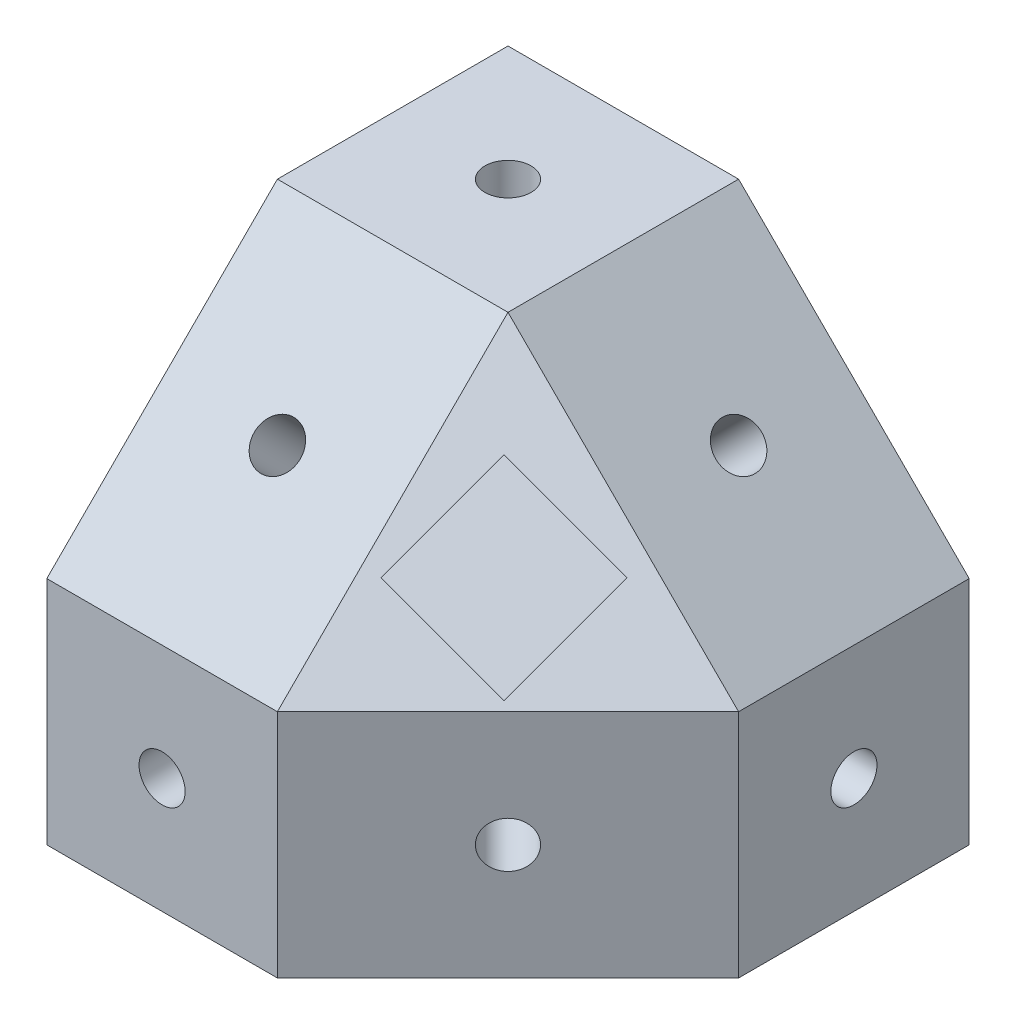
SolidWorks part; units mm, degrees
ref_plane "Front Plane" through (0, 0, 0) normal (0, 0, 1) x (1, 0, 0)
ref_plane "Top Plane" through (0, 0, 0) normal (0, 1, 0) x (1, 0, 0)
ref_plane "Right Plane" through (0, 0, 0) normal (1, 0, 0) x (0, 0, -1)
sketch "Sketch1" plane through (0, 0, 0) normal (0, 0, 1) x (1, 0, 0)
  line L1 (0, 0) -> (30, 0)
  line L2 (0, 0) -> (0, 30)
  line L3 (0, 30) -> (30, 30)
  line L4 (30, 0) -> (30, 30)
  dimension "D1" = 30
  dimension "D2" = 30
extrude "Boss-Extrude1" add sketch "Sketch1" against normal blind 30
sketch "Sketch2" plane through (0, 0, 0) normal (0, 0, 1) x (1, 0, 0)
  line L0 (15, 30) -> (30, 15)
  line L1 (30, 30) -> (0, 30) construction
  line L2 (30, 0) -> (30, 30) construction
  line L3 (30, 15) -> (45, 15)
  line L4 (45, 15) -> (45, 45.6191)
  line L5 (45, 45.6191) -> (15, 40.3683)
  line L6 (15, 40.3683) -> (15, 30)
  dimension "D1" = 15
  dimension "D2" = 15
  dimension "D3" = 15
extrude "Cut-Extrude1" cut sketch "Sketch2" against normal blind 30
sketch "Sketch3" plane through (0, 0, 0) normal (-1, 0, 0) x (0, 0, 1)
  line L0 (0, 15) -> (-15, 30)
  line L1 (0, 30) -> (0, 0) construction
  line L2 (-30, 30) -> (0, 30) construction
  line L3 (-15, 30) -> (-15, 36.1773)
  line L4 (-15, 36.1773) -> (9.5396, 36.1773)
  line L5 (9.5396, 36.1773) -> (9.5396, 15)
  line L6 (9.5396, 15) -> (0, 15)
  dimension "D1" = 15
extrude "Cut-Extrude2" cut sketch "Sketch3" against normal blind 30
sketch "Sketch4" plane through (0, 0, 0) normal (0, -1, 0) x (1, 0, 0)
  line L0 (15, 0) -> (30, -15)
  line L1 (0, 0) -> (30, 0) construction
  line L2 (30, -30) -> (30, 0) construction
  line L3 (30, -15) -> (40.2278, -15)
  line L4 (40.2278, -15) -> (40.2278, 9.3171)
  line L5 (40.2278, 9.3171) -> (15, 8.9664)
  line L6 (15, 8.9664) -> (15, 0)
extrude "Cut-Extrude3" cut sketch "Sketch4" against normal blind 30
sketch3d "3DSketch1"
  line L1 (33.9969, 3.57, -7.567) -> (10, 10, 10)
  line L2 (33.9969, 3.57, -7.567) -> (45.4692, 15.0424, 3.9054)
  line L3 (45.4692, 15.0424, 3.9054) -> (21.4723, 21.4723, 21.4723)
  line L4 (10, 10, 10) -> (21.4723, 21.4723, 21.4723)
  point P7 (32.9904, 3.8397, -6.8301)
  point P8 (32.9904, 3.8397, -6.8301)
  point P9 (32.9904, 3.8397, -6.8301)
  point P10 (32.9904, 3.8397, -6.8301)
  dimension "D1" = 0
extrude "Cut-Extrude4" cut sketch "3DSketch1" along a picked direction on the side of the normal blind 30
sketch "Sketch5" plane through (10, 10, 10) normal (0.5774, 0.5774, 0.5774) x (0.4082, 0.4082, -0.8165)
  line L0 (19.4571, 2.9469) -> (27.1845, 5.0174)
  line L1 (27.1845, 5.0174) -> (29.255, -2.71)
  line L2 (29.255, -2.71) -> (21.5276, -4.7806)
  line L3 (21.5276, -4.7806) -> (19.4571, 2.9469)
  line L4 (12.2474, 0) -> (30.6186, -10.6066) construction
  dimension "D1" = 8
  dimension "D2" = 8
  dimension "D3" = 0.5
  dimension "D4" = 45
extrude "Cut-Extrude5" cut sketch "Sketch5" against normal blind 15
sketch "Sketch6" plane through (0, 30, 0) normal (0, 1, 0) x (1, 0, 0)
  line L0 (15, 30) -> (0, 30) construction
  line L1 (0, 30) -> (0, 15) construction
  circle A0 centre (7.5, 22.5) radius 1.5
  point P4 (7.5, 30)
  dimension "D1" = 3
  dimension "D2" = 7.5
  dimension "D3" = 7.5
sketch "Sketch7" plane through (0, 7.5, 7.5) normal (0, 0.7071, 0.7071) x (1, 0, 0)
  line L0 (15, 31.8198) -> (15, 10.6066) construction
  circle A0 centre (7.5, 21.2132) radius 1.5
  point P0 (7.5, 21.2132)
  point P3 (15, 21.2132)
  dimension "D1" = 0
sketch "Sketch8" plane through (0, 0, 0) normal (0, 0, 1) x (1, 0, 0)
  line L0 (0, 15) -> (0, 0) construction
  line L1 (0, 0) -> (15, 0) construction
  circle A0 centre (7.5, 7.5) radius 1.5
  dimension "D1" = 3
  dimension "D2" = 7.5
  dimension "D3" = 7.5
sketch "Sketch9" plane through (22.5, 22.5, 0) normal (0.7071, 0.7071, 0) x (0, 0, -1)
  line L0 (30, -10.6066) -> (15, -10.6066) construction
  line L1 (30, 10.6066) -> (30, -10.6066) construction
  circle A0 centre (22.5, -0.0016) radius 1.5
  dimension "D1" = 3
  dimension "D2" = 10.605
  dimension "D3" = 7.5
sketch "Sketch10" plane through (30, 0, 0) normal (1, 0, 0) x (0, 0, -1)
  line L0 (30, 0) -> (30, 15) construction
  line L1 (30, 0) -> (15, 0) construction
  circle A0 centre (22.5, 7.5) radius 1.5
  dimension "D1" = 3
  dimension "D2" = 7.5
  dimension "D3" = 7.5
sketch "Sketch11" plane through (7.5, 0, 7.5) normal (0.7071, 0, 0.7071) x (0.7071, 0, -0.7071)
  line L0 (10.6066, 15) -> (10.6066, 0) construction
  line L1 (10.6066, 0) -> (31.8198, 0) construction
  circle A0 centre (21.2116, 7.5) radius 1.5
  dimension "D1" = 10.605
  dimension "D3" = 3
  dimension "D2" = 7.5
extrude "Cut-Extrude6" cut sketch "Sketch6" against normal blind 10 contours A0
extrude "Cut-Extrude7" cut sketch "Sketch7" against normal blind 10
extrude "Cut-Extrude8" cut sketch "Sketch8" against normal blind 10
extrude "Cut-Extrude9" cut sketch "Sketch9" against normal blind 10
extrude "Cut-Extrude10" cut sketch "Sketch10" against normal blind 10
extrude "Cut-Extrude11" cut sketch "Sketch11" against normal blind 10
